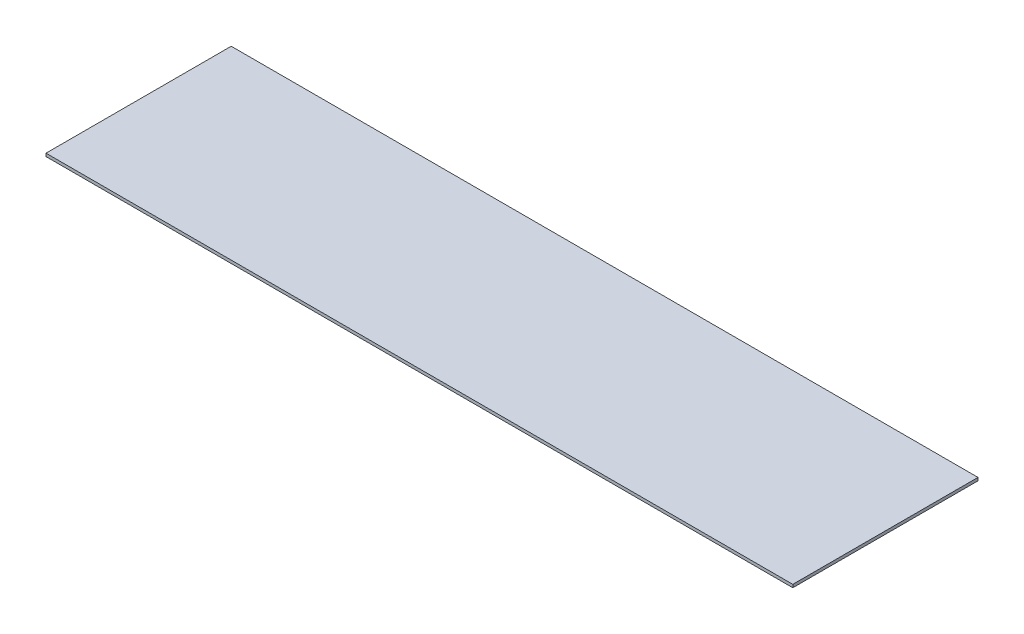
SolidWorks part; units mm, degrees
ref_plane "Front Plane" through (0, 0, 0) normal (0, 0, 1) x (1, 0, 0)
ref_plane "Top Plane" through (0, 0, 0) normal (0, 1, 0) x (1, 0, 0)
ref_plane "Right Plane" through (0, 0, 0) normal (1, 0, 0) x (0, 0, -1)
sketch "Sketch2" plane through (0, 0, 0) normal (0, 1, 0) x (1, 0, 0)
  line L1 (-111.4894, -19.4574) -> (138.5106, -19.4574)
  line L2 (-111.4894, -19.4574) -> (-111.4894, -81.4574)
  line L3 (-111.4894, -81.4574) -> (138.5106, -81.4574)
  line L4 (138.5106, -19.4574) -> (138.5106, -81.4574)
  dimension "D1" = 62
  dimension "D2" = 250
extrude "Boss-Extrude1" add sketch "Sketch2" along normal blind 1
